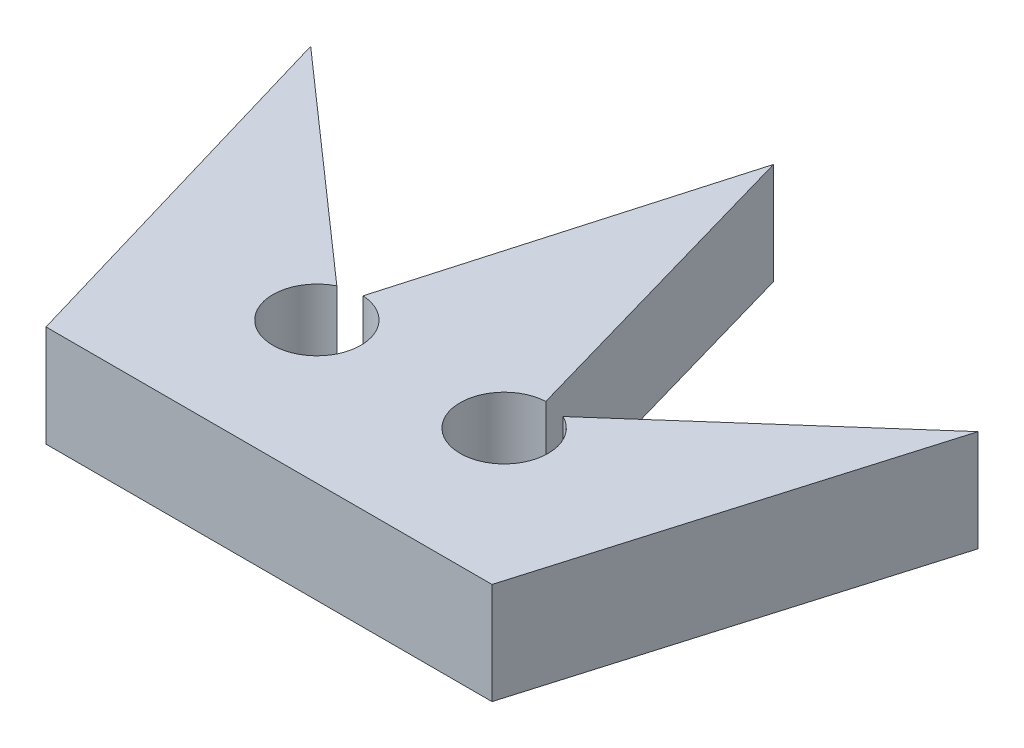
SolidWorks part; units mm, degrees
ref_plane "Front Plane" through (0, 0, 0) normal (0, 0, 1) x (1, 0, 0)
ref_plane "Top Plane" through (0, 0, 0) normal (0, 1, 0) x (1, 0, 0)
ref_plane "Right Plane" through (0, 0, 0) normal (1, 0, 0) x (0, 0, -1)
sketch "Sketch1" plane through (0, 0, 0) normal (0, 1, 0) x (1, 0, 0)
  line L0 (-157.1448, -59.5486) -> (9.5219, -59.5486) construction
  line L1 (3.7784, 36.5616) -> (3.7784, -43.3315) construction
  line L2 (33.9115, -31.6077) -> (48.863, 19.1063)
  line L3 (48.863, 19.1063) -> (19.061, -7.1599)
  line L4 (16.1313, -6.5537) -> (3.7784, 36.5616)
  line L5 (33.9115, -31.6077) -> (-26.3547, -31.6077)
  line L6 (-26.3547, -31.6077) -> (-41.3062, 19.1063)
  line L7 (-41.3062, 19.1063) -> (-11.5041, -7.1599)
  line L8 (-8.5744, -6.5537) -> (3.7784, 36.5616)
  arc A0 (19.061, -7.1599) -> (16.1313, -6.5537) centre (16.4306, -12.49) cw
  arc A1 (-11.5041, -7.1599) -> (-8.5744, -6.5537) centre (-8.8738, -12.49) ccw
  point P11 (3.7784, -31.6077)
extrude "Boss-Extrude1" add sketch "Sketch1" along normal blind 13.716
scale "Scale1" bodies to scale 101 scale about centroid uniform scaling yes scale factor 1.5
